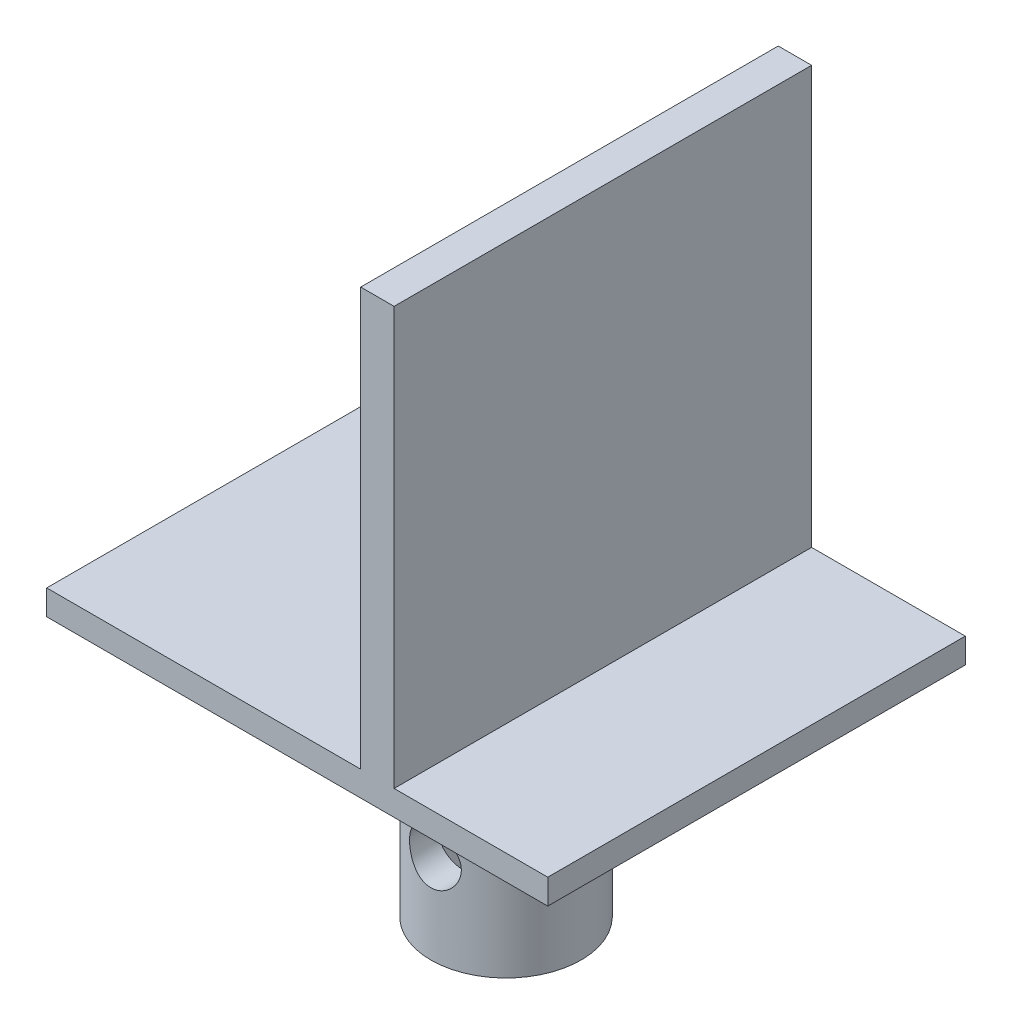
SolidWorks part; units mm, degrees
ref_plane "前视基准面" through (0, 0, 0) normal (0, 0, 1) x (1, 0, 0)
ref_plane "上视基准面" through (0, 0, 0) normal (0, 1, 0) x (1, 0, 0)
ref_plane "右视基准面" through (0, 0, 0) normal (1, 0, 0) x (0, 0, -1)
other "Configuration Table"
sketch "草图1" plane through (0, 0, 0) normal (0, 1, 0) x (1, 0, 0)
  line L0 (-38.4708, 0) -> (36.9052, 0) construction
  line L1 (0, 33.6043) -> (0, -32.9499) construction
  circle A0 centre (0, 0) radius 3.1
  circle A1 centre (0, 0) radius 4.5
  dimension "D1" = 6.2
  dimension "D2" = 9
extrude "凸台-拉伸1" add sketch "草图1" along normal blind 14.3
sketch "草图2" plane through (0, 14.3, 0) normal (0, 1, 0) x (1, 0, 0)
  line L0 (-1.6882, -2.6) -> (1.6882, -2.6)
  circle A0 centre (0, 0) radius 3.1 construction
  arc A1 (-1.6882, -2.6) -> (1.6882, -2.6) centre (0, 0) ccw
  dimension "D1" = 2.6
extrude "凸台-拉伸2" add sketch "草图2" against normal blind 11.25
sketch "草图3" plane through (0, 0, 0) normal (0, 0, 1) x (1, 0, 0)
  line L0 (0, 18.6138) -> (0, -3.9404) construction
  line L1 (4.5, 14.3) -> (-4.5, 14.3) construction
  circle A0 centre (0, 5.3) radius 1.55
  dimension "D1" = 3.1
  dimension "D2" = 9
extrude "切除-拉伸1" cut sketch "草图3" against normal through all and the other way through all
sketch "草图4" plane through (0, 14.3, 0) normal (0, 1, 0) x (1, 0, 0)
  line L1 (-15, -12.5) -> (15, -12.5)
  line L2 (-15, -12.5) -> (-15, 12.5)
  line L3 (-15, 12.5) -> (15, 12.5)
  line L4 (15, -12.5) -> (15, 12.5)
  line L5 (-15, -12.5) -> (15, 12.5) construction
  line L6 (-15, 12.5) -> (15, -12.5) construction
  point P0 (0, 0)
  dimension "D1" = 25
  dimension "D2" = 30
extrude "凸台-拉伸3" add sketch "草图4" along normal blind 1.5
sketch "草图5" plane through (0, 15.8, 0) normal (0, 1, 0) x (1, 0, 0)
  circle A0 centre (0, 0) radius 1.6
  dimension "D1" = 3.2
extrude "切除-拉伸2" cut sketch "草图5" against normal through all
sketch "草图6" plane through (0, 15.8, 0) normal (0, 1, 0) x (1, 0, 0)
  line L0 (3.8, 12.5) -> (3.8, -12.5)
  line L1 (15, 12.5) -> (-15, 12.5) construction
  line L2 (-15, -12.5) -> (15, -12.5) construction
  line L3 (3.8, -12.5) -> (5.8, -12.5)
  line L4 (5.8, -12.5) -> (5.8, 12.5)
  line L5 (5.8, 12.5) -> (3.8, 12.5)
  line L6 (15, -12.5) -> (15, 12.5) construction
  dimension "D1" = 9.2
  dimension "D2" = 2
extrude "凸台-拉伸4" add sketch "草图6" along normal blind 25
